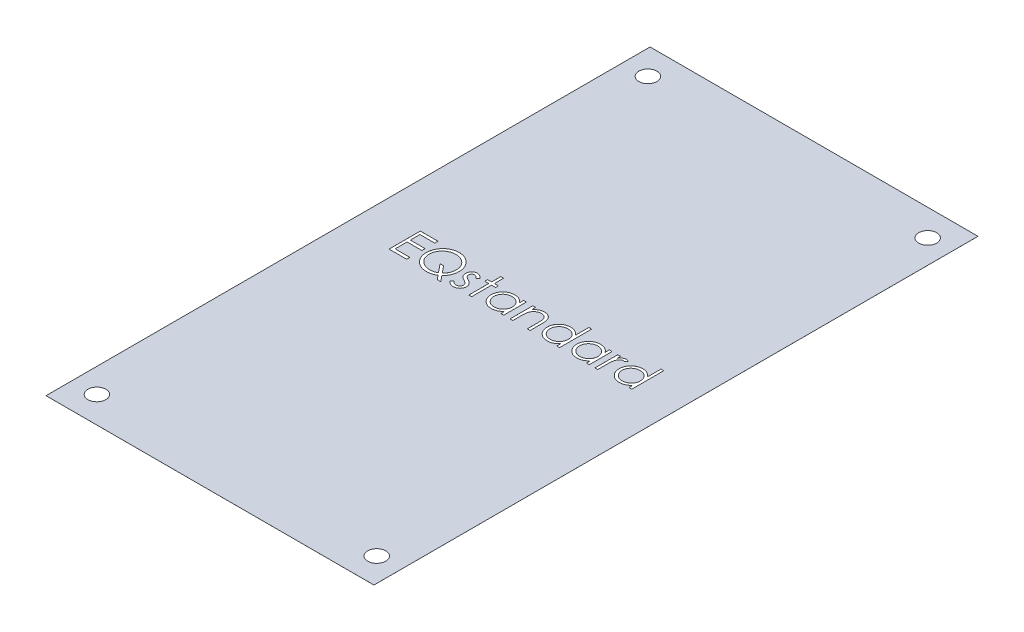
SolidWorks part; units mm, degrees
ref_plane "Front Plane" through (0, 0, 0) normal (0, 0, 1) x (1, 0, 0)
ref_plane "Top Plane" through (0, 0, 0) normal (0, 1, 0) x (1, 0, 0)
ref_plane "Right Plane" through (0, 0, 0) normal (1, 0, 0) x (0, 0, -1)
sketch "Sketch2" plane through (0, 0, 0) normal (0, 1, 0) x (1, 0, 0)
  line L1 (-33.3375, -61.4045) -> (33.3375, -61.4045)
  line L2 (-33.3375, -61.4045) -> (-33.3375, 61.4045)
  line L3 (-33.3375, 61.4045) -> (33.3375, 61.4045)
  line L4 (33.3375, -61.4045) -> (33.3375, 61.4045)
  line L5 (-33.3375, -61.4045) -> (33.3375, 61.4045) construction
  line L6 (-33.3375, 61.4045) -> (33.3375, -61.4045) construction
  point P0 (0, 0)
  dimension "D1" = 122.809
  dimension "D2" = 66.675
extrude "Boss-Extrude1" add sketch "Sketch2" along normal blind 0.0025
sketch "Sketch3" plane through (0, 0.0025, 0) normal (0, 1, 0) x (1, 0, 0)
  line L1 (-28.3845, -56.007) -> (28.3845, -56.007)
  line L2 (-28.3845, -56.007) -> (-28.3845, 56.007)
  line L3 (-28.3845, 56.007) -> (28.3845, 56.007)
  line L4 (28.3845, -56.007) -> (28.3845, 56.007)
  line L5 (-28.3845, -56.007) -> (28.3845, 56.007) construction
  line L6 (-28.3845, 56.007) -> (28.3845, -56.007) construction
  circle A0 centre (-28.3845, 56.007) radius 1.8288
  circle A7 centre (28.5115, 56.007) radius 1.8288
  circle A8 centre (28.5115, -56.007) radius 1.8288
  circle A9 centre (-28.3845, -56.007) radius 1.8288
  point P0 (0, 0)
  dimension "D3" = 3.6576
  dimension "D1" = 112.014
  dimension "D2" = 56.769
  dimension "D4" = 2
  dimension "D5" = 2
extrude "Cut-Extrude1" cut sketch "Sketch3" against normal through all contours A9 | A8 | A7 | A0
sketch "Sketch5" plane through (0, 0.0025, 0) normal (0, 1, 0) x (1, 0, 0)
  text T0 "EQstandard" font "Century Gothic" height 6.35
  point P1 (-23.0976, -2.5229)
extrude "Cut-Extrude2" cut sketch "Sketch5" against normal blind 2.54
